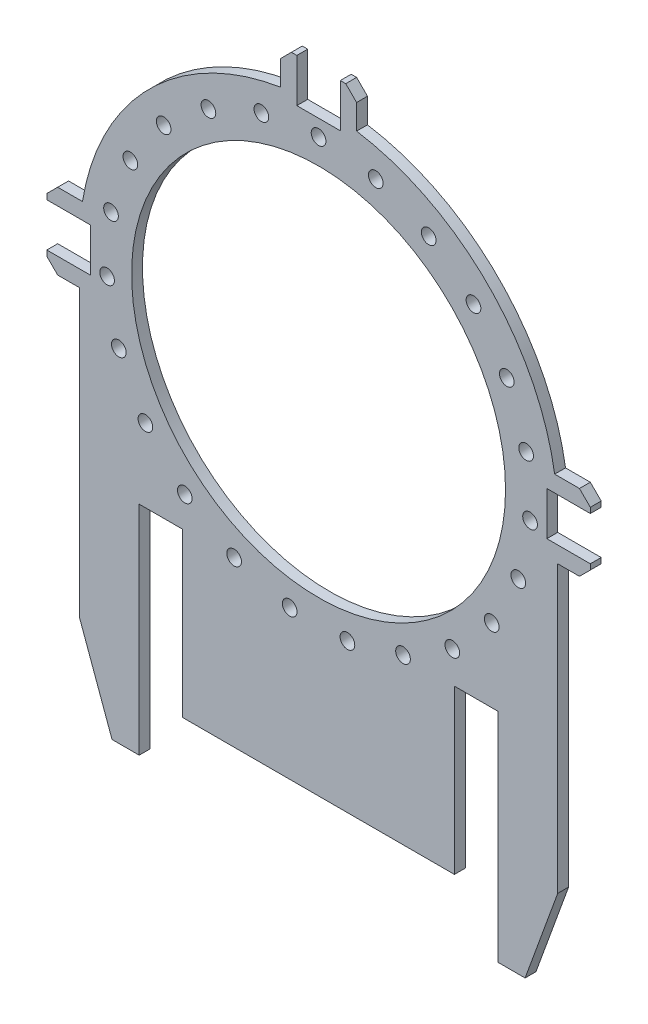
SolidWorks part; units mm, degrees
ref_plane "Plan de face" through (0, 0, 0) normal (0, 0, 1) x (1, 0, 0)
ref_plane "Plan de dessus" through (0, 0, 0) normal (0, 1, 0) x (1, 0, 0)
ref_plane "Plan de droite" through (0, 0, 0) normal (1, 0, 0) x (0, 0, -1)
sketch "Esquisse1" plane through (0, 0, 0) normal (0, 0, 1) x (1, 0, 0)
  line L0 (0, 195) -> (0, 0) construction
  line L1 (0, 0) -> (0, -220) construction
  line L2 (220, -35) -> (220, -297.5757)
  line L3 (190, -380) -> (165, -380)
  line L4 (165, -380) -> (165, -180)
  line L5 (165, -180) -> (125, -180)
  line L6 (125, -180) -> (125, -330)
  line L7 (125, -330) -> (-125, -330)
  line L8 (0, -220) -> (0, -330) construction
  line L9 (-220, -35) -> (-220, -297.5757)
  line L10 (-190, -380) -> (-165, -380)
  line L11 (-165, -380) -> (-165, -180)
  line L12 (-165, -180) -> (-125, -180)
  line L13 (-125, -180) -> (-125, -330)
  line L14 (220, -297.5757) -> (190, -380)
  line L15 (-220, -297.5757) -> (-190, -380)
  line L16 (220, 0) -> (-220, 0) construction
  line L17 (-20, 250) -> (-25, 250)
  line L18 (-35, 240) -> (-35, 217.1981)
  line L19 (20, 250) -> (25, 250)
  line L20 (35, 240) -> (35, 217.1981)
  line L21 (-25, 250) -> (-35, 240)
  line L22 (25, 250) -> (35, 240)
  line L23 (210, 20) -> (210, -20)
  line L24 (250, -20) -> (210, -20)
  line L25 (240, -35) -> (220, -35)
  line L26 (-20, 250) -> (20, 250) construction
  line L27 (-20, 250) -> (-20, 210)
  line L28 (-20, 210) -> (20, 210)
  line L29 (20, 250) -> (20, 210)
  line L30 (250, -25) -> (240, -35)
  line L31 (250, -20) -> (250, -25)
  line L32 (250, 20) -> (250, 25)
  line L33 (250, 25) -> (240, 35)
  line L34 (240, 35) -> (217.1981, 35)
  line L35 (250, 20) -> (210, 20)
  line L45 (-210, -20) -> (-210, 20)
  line L46 (-250, 20) -> (-210, 20)
  line L47 (-240, 35) -> (-217.1981, 35)
  line L48 (-250, 25) -> (-240, 35)
  line L49 (-250, 20) -> (-250, 25)
  line L50 (-250, -20) -> (-250, -25)
  line L51 (-250, -25) -> (-240, -35)
  line L52 (-240, -35) -> (-220, -35)
  line L53 (-250, -20) -> (-210, -20)
  line L54 (20, -250) -> (25, -250) [skipped]
  line L55 (25, -250) -> (35, -240) [skipped]
  line L56 (35, -240) -> (35, -217.1981) [skipped]
  line L57 (20, -250) -> (20, -210) [skipped]
  line L58 (-25, -250) -> (-35, -240) [skipped]
  line L59 (-20, -250) -> (-25, -250) [skipped]
  line L60 (-20, -250) -> (-20, -210) [skipped]
  line L61 (-35, -240) -> (-35, -217.1981) [skipped]
  line L62 (20, -210) -> (-20, -210) [skipped]
  circle A0 centre (0, 0) radius 195 construction
  circle A1 centre (0, 195) radius 6.75
  arc A2 (-35, 217.1981) -> (35, 217.1981) centre (0, 0) cw construction
  circle A3 centre (0, 0) radius 172
  circle A4 centre (52.6104, 187.7689) radius 6.75
  circle A5 centre (101.3189, 166.6118) radius 6.75
  circle A6 centre (142.513, 133.0979) radius 6.75
  circle A7 centre (173.1376, 89.7127) radius 6.75
  circle A8 centre (190.9214, 39.6739) radius 6.75
  circle A9 centre (194.5454, -13.3073) radius 6.75
  circle A10 centre (183.7409, -65.3015) radius 6.75
  circle A11 centre (159.3091, -112.4527) radius 6.75
  circle A12 centre (123.0621, -151.2637) radius 6.75
  circle A13 centre (77.6882, -178.8562) radius 6.75
  circle A14 centre (26.5525, -193.1838) radius 6.75
  circle A15 centre (-26.5525, -193.1838) radius 6.75
  circle A16 centre (-77.6882, -178.8562) radius 6.75
  circle A17 centre (-123.0621, -151.2637) radius 6.75
  circle A18 centre (-159.3091, -112.4527) radius 6.75
  circle A19 centre (-183.7409, -65.3015) radius 6.75
  circle A20 centre (-194.5454, -13.3073) radius 6.75
  circle A21 centre (-190.9214, 39.6739) radius 6.75
  circle A22 centre (-173.1376, 89.7127) radius 6.75
  circle A23 centre (-142.513, 133.0979) radius 6.75
  circle A24 centre (-101.3189, 166.6118) radius 6.75
  circle A25 centre (-52.6104, 187.7689) radius 6.75
  arc A26 (218.2315, -20) -> (0, -219.1461) centre (0, 0) cw construction
  arc A27 (-35, 217.1981) -> (-217.1981, 35) centre (0, 0) ccw
  arc A28 (217.1981, 35) -> (35, 217.1981) centre (0, 0) ccw
  point P9 (220, -380)
  point P54 (0, 0)
  point P60 (-220, -380)
  point P71 (-35, 250)
  point P73 (35, 250)
  point P78 (207.8614, 0)
  point P79 (-201.9645, 0)
  point P84 (0, 210)
  point P86 (0, 0)
  point P118 (0, 0)
  dimension "D1" = 390
  dimension "D2" = 13.5
  dimension "D3" = 440
  dimension "D4" = 344
  dimension "D6" = 40
  dimension "D7" = 330
  dimension "D8" = 200
  dimension "D9" = 50
  dimension "D10" = 30
  dimension "D11" = 70
  dimension "D12" = 30
  dimension "D13" = 70
  dimension "D14" = 210
  dimension "D15" = 15
  dimension "D16" = 15
  dimension "D17" = 4
  dimension "D18" = 40
  dimension "D19" = 40
  dimension "D20" = 20
  dimension "D21" = 210
  dimension "D22" = 330
  dimension "D5" = 23
extrude "Boss.-Extru.1" add sketch "Esquisse1" along normal blind 10
